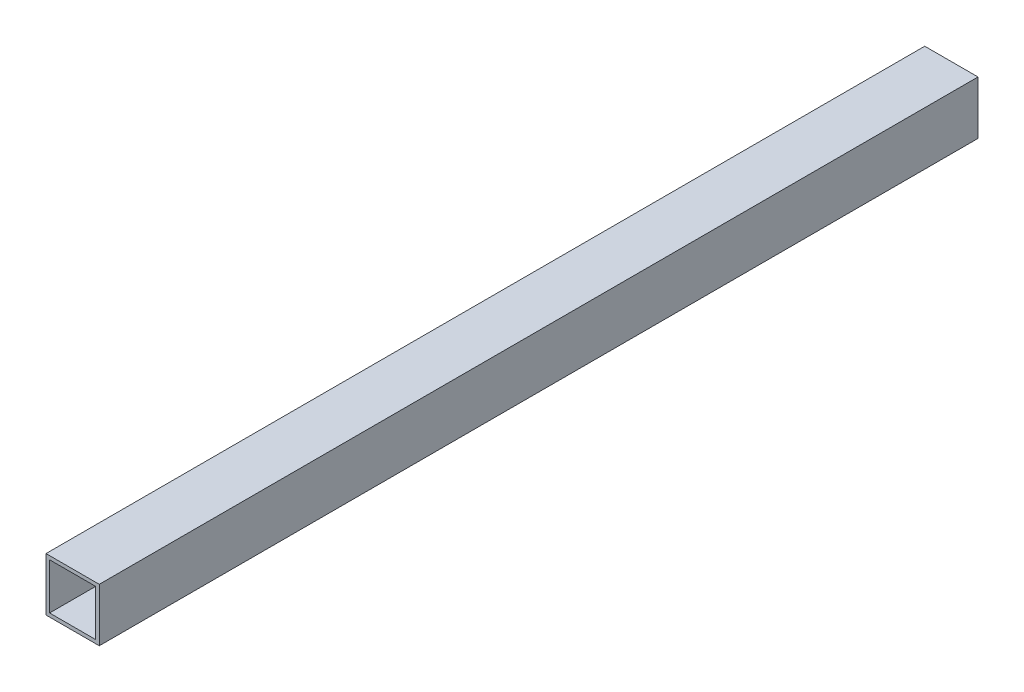
SolidWorks part; units mm, degrees
material "6063-O, Extruded Rod (SS)"
ref_plane "Front Plane" through (0, 0, 0) normal (0, 0, 1) x (1, 0, 0)
ref_plane "Top Plane" through (0, 0, 0) normal (0, 1, 0) x (1, 0, 0)
ref_plane "Right Plane" through (0, 0, 0) normal (1, 0, 0) x (0, 0, -1)
sketch "Sketch1" plane through (0, 0, 0) normal (0, 0, 1) x (1, 0, 0)
  line L0 (-10.9855, 10.9855) -> (10.9855, 10.9855)
  line L1 (-12.7, -12.7) -> (12.7, -12.7)
  line L2 (-12.7, -12.7) -> (-12.7, 12.7)
  line L3 (-12.7, 12.7) -> (12.7, 12.7)
  line L4 (12.7, -12.7) -> (12.7, 12.7)
  line L5 (-12.7, -12.7) -> (12.7, 12.7) construction
  line L6 (-12.7, 12.7) -> (12.7, -12.7) construction
  line L7 (10.9855, -10.9855) -> (10.9855, 10.9855)
  line L8 (-10.9855, -10.9855) -> (10.9855, -10.9855)
  line L9 (-10.9855, -10.9855) -> (-10.9855, 10.9855)
  point P0 (0, 0)
  dimension "D1" = 25.4
  dimension "D2" = 25.4
  dimension "D3" = 1.7145
extrude "Boss-Extrude1" add sketch "Sketch1" along normal mid plane 419.1
